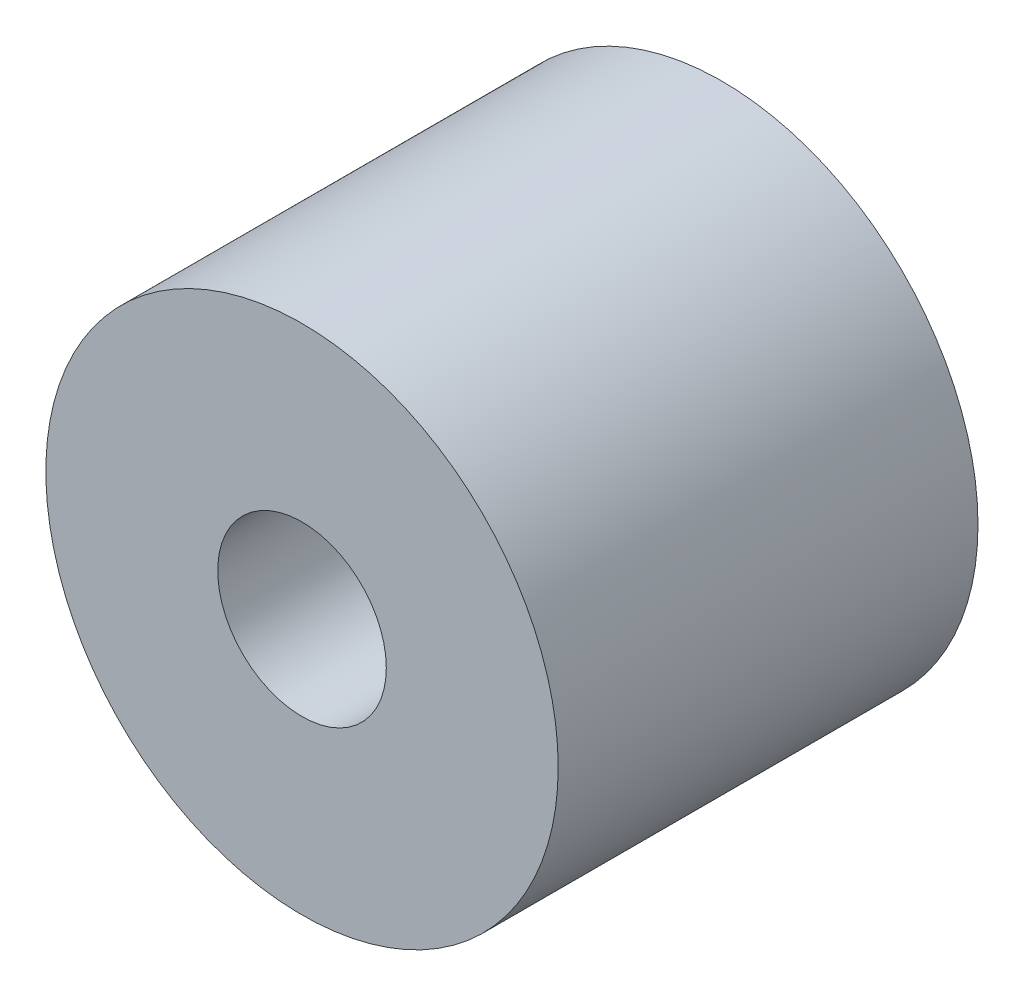
SolidWorks part; units mm, degrees
ref_plane "Front Plane" through (0, 0, 0) normal (0, 0, 1) x (1, 0, 0)
ref_plane "Top Plane" through (0, 0, 0) normal (0, 1, 0) x (1, 0, 0)
ref_plane "Right Plane" through (0, 0, 0) normal (1, 0, 0) x (0, 0, -1)
sketch "Sketch1" plane through (0, 0, 0) normal (0, 0, 1) x (1, 0, 0)
  circle A0 centre (0, 0) radius 2.55
  circle A1 centre (0, 0) radius 7.75
  dimension "D1" = 5.1
  dimension "D2" = 15.5
extrude "Boss-Extrude1" add sketch "Sketch1" along normal mid plane 12.7
